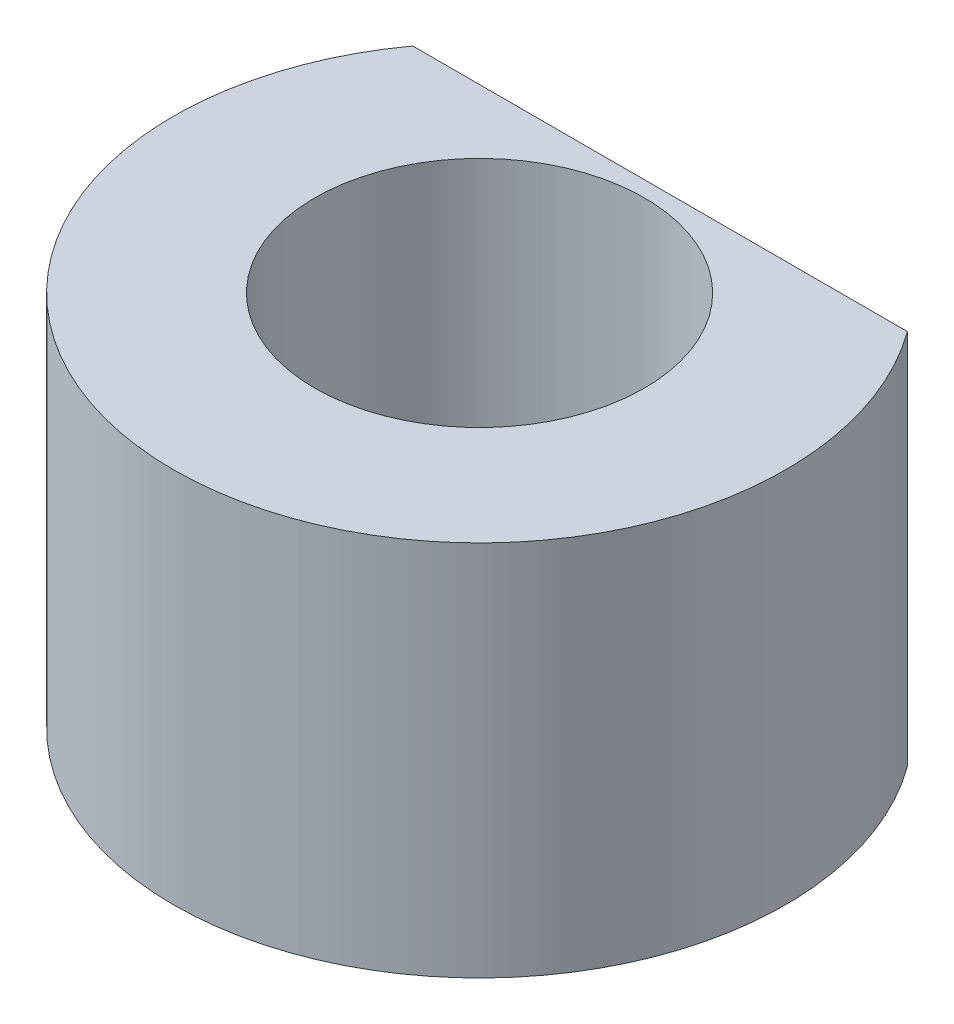
SolidWorks part; units mm, degrees
ref_plane "Front Plane" through (0, 0, 0) normal (0, 0, 1) x (1, 0, 0)
ref_plane "Top Plane" through (0, 0, 0) normal (0, 1, 0) x (1, 0, 0)
ref_plane "Right Plane" through (0, 0, 0) normal (1, 0, 0) x (0, 0, -1)
sketch "Sketch1" plane through (0, 0, 0) normal (0, 1, 0) x (1, 0, 0)
  line L0 (-1.575, 1.1497) -> (1.575, 1.1497)
  circle A0 centre (0, 0) radius 1.95
  dimension "D1" = 3.9
  dimension "D2" = 3.15
extrude "Boss-Extrude1" add sketch "Sketch1" along normal blind 2.4 contours L0 A0
sketch "Sketch2" plane through (0, 2.4, 0) normal (0, 1, 0) x (1, 0, 0)
  circle A0 centre (0, 0) radius 1.05
  dimension "D1" = 2.1
extrude "Cut-Extrude1" cut sketch "Sketch2" against normal through all
